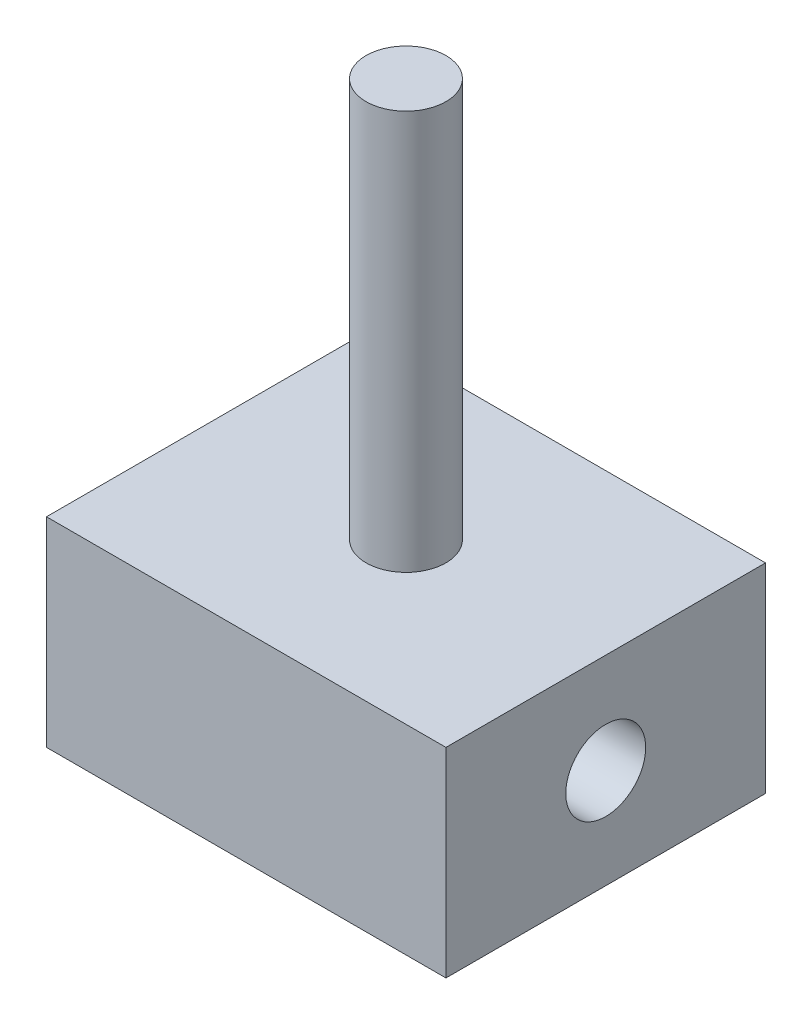
SolidWorks part; units mm, degrees
ref_plane "Front Plane" through (0, 0, 0) normal (0, 0, 1) x (1, 0, 0)
ref_plane "Top Plane" through (0, 0, 0) normal (0, 1, 0) x (1, 0, 0)
ref_plane "Right Plane" through (0, 0, 0) normal (1, 0, 0) x (0, 0, -1)
sketch "Sketch1" plane through (0, 0, 0) normal (0, 0, 1) x (1, 0, 0)
  line L0 (0, 25) -> (0, 75) construction
  line L1 (-25, 0) -> (25, 0)
  line L2 (-25, 0) -> (-25, 25)
  line L3 (-25, 25) -> (25, 25)
  line L4 (25, 0) -> (25, 25)
  line L6 (-25, 100) -> (25, 100)
  line L7 (-25, 100) -> (-25, 75)
  line L8 (-25, 75) -> (25, 75)
  line L9 (25, 100) -> (25, 75)
  point P4 (0, 0)
  point P12 (0, 75)
  dimension "D1" = 50
  dimension "D2" = 25
  dimension "D3" = 50
  dimension "D4" = 25
  dimension "D5" = 50
extrude "Boss-Extrude1" add sketch "Sketch1" along normal mid plane 40 contours L1 L4 L3 L2
sketch "Sketch4" plane through (0, 25, 0) normal (0, 1, 0) x (1, 0, 0)
  circle A0 centre (0, 0) radius 5
  dimension "D1" = 10
extrude "Boss-Extrude2" add sketch "Sketch4" along normal blind 50
sketch "Sketch5" plane through (0, 75, 0) normal (0, 1, 0) x (1, 0, 0)
  line L0 (0, 0) -> (5, 0) construction
  circle A1 centre (0, 0) radius 5
  circle A2 centre (0, 0) radius 5
  dimension "D1" = 0
sketch "Sketch6" plane through (25, 0, 0) normal (1, 0, 0) x (0, 0, -1)
  line L0 (0, 25) -> (0, 0) construction
  line L4 (20, 0) -> (20, 25)
  line L5 (20, 25) -> (-20, 25)
  line L6 (-20, 25) -> (-20, 0)
  line L7 (-20, 0) -> (20, 0)
  line L8 (20, 0) -> (20, 25)
  line L9 (20, 25) -> (-20, 25)
  line L10 (-20, 25) -> (-20, 0)
  line L11 (-20, 0) -> (20, 0)
  circle A0 centre (0, 12.5) radius 5
  point P9 (0, 18.2223)
  point P10 (0, 12.5)
  dimension "D2" = 10
  dimension "D1" = 0
extrude "Cut-Extrude1" cut sketch "Sketch6" against normal blind 50 contours L0 A0 | A0 L0
